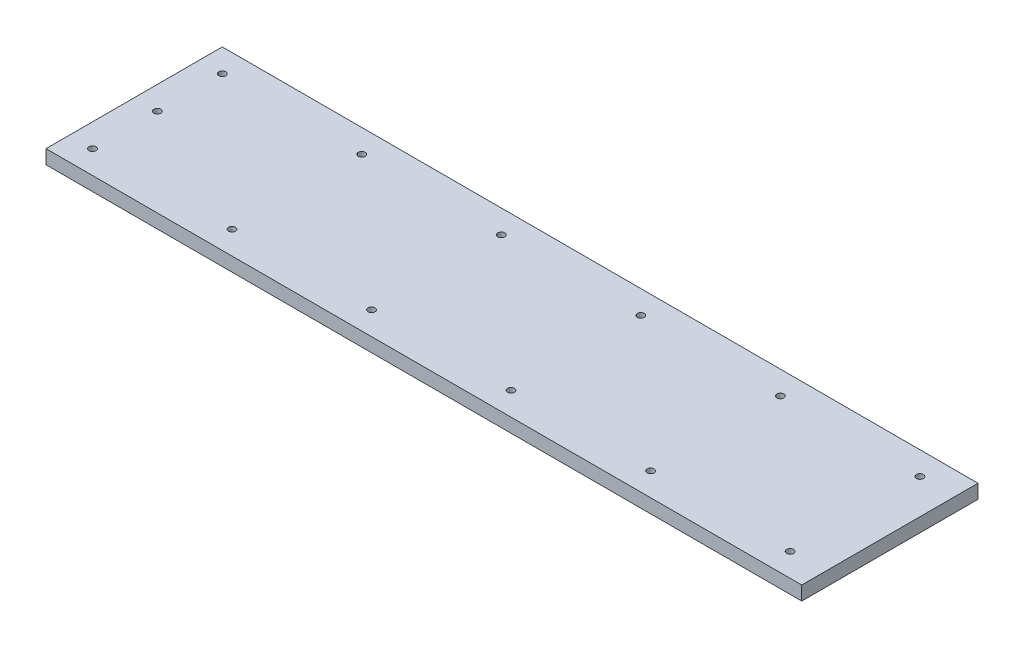
SolidWorks part; units mm, degrees
ref_plane "前视基准面" through (0, 0, 0) normal (0, 0, 1) x (1, 0, 0)
ref_plane "上视基准面" through (0, 0, 0) normal (0, 1, 0) x (1, 0, 0)
ref_plane "右视基准面" through (0, 0, 0) normal (1, 0, 0) x (0, 0, -1)
sketch "草图1" plane through (0, 0, 0) normal (0, 1, 0) x (1, 0, 0)
  line L0 (-162.5, -0.8) -> (162.5, -0.8) construction
  line L1 (-162.5, 65) -> (162.5, 65)
  line L2 (-162.5, 65) -> (-162.5, -10.8)
  line L3 (-162.5, -10.8) -> (162.5, -10.8)
  line L4 (162.5, 65) -> (162.5, -10.8)
  line L5 (-162.5, 55) -> (162.5, 55) construction
  line L6 (-152.5, 65) -> (-152.5, -10.8) construction
  circle A0 centre (-152.5, 55) radius 1.5
  circle A1 centre (-152.5, -0.8) radius 1.5
  circle A2 centre (-92.5, 55) radius 1.5
  circle A3 centre (-32.5, 55) radius 1.5
  circle A4 centre (27.5, 55) radius 1.5
  circle A5 centre (87.5, 55) radius 1.5
  circle A6 centre (147.5, 55) radius 1.5
  circle A7 centre (-92.5, -0.8) radius 1.5
  circle A8 centre (-32.5, -0.8) radius 1.5
  circle A9 centre (27.5, -0.8) radius 1.5
  circle A10 centre (87.5, -0.8) radius 1.5
  circle A11 centre (147.5, -0.8) radius 1.5
  circle A12 centre (-152.5, 27.1) radius 1.5
  dimension "D8" = 3
  dimension "D9" = 3
  dimension "D12" = 3
  dimension "D1" = 325
  dimension "D2" = 75.8
  dimension "D3" = 65
  dimension "D4" = 162.5
  dimension "D5" = 10
  dimension "D6" = 10
  dimension "D7" = 10
  dimension "D10" = 6
  dimension "D11" = 6
extrude "凸台-拉伸1" add sketch "草图1" along normal blind 6
